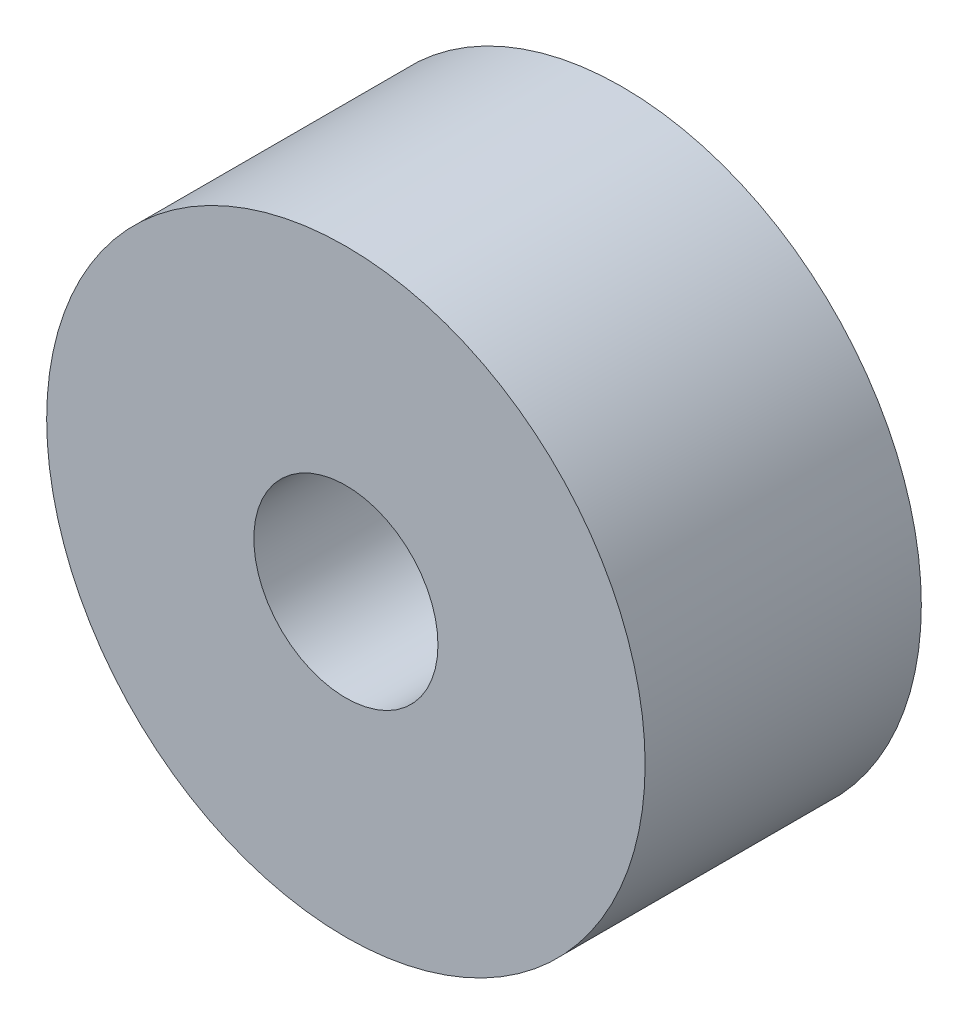
SolidWorks part; units mm, degrees
ref_plane "Front Plane" through (0, 0, 0) normal (0, 0, 1) x (1, 0, 0)
ref_plane "Top Plane" through (0, 0, 0) normal (0, 1, 0) x (1, 0, 0)
ref_plane "Right Plane" through (0, 0, 0) normal (1, 0, 0) x (0, 0, -1)
sketch "Sketch1" plane through (0, 0, 0) normal (0, 0, 1) x (1, 0, 0)
  circle A0 centre (0, 0) radius 6.5
  dimension "D1" = 13
extrude "Boss-Extrude1" add sketch "Sketch1" along normal blind 6
sketch "Sketch2" plane through (0, 0, 6) normal (0, 0, 1) x (1, 0, 0)
  circle A0 centre (0, 0) radius 2
  dimension "D1" = 4
extrude "Cut-Extrude1" cut sketch "Sketch2" against normal blind 6
